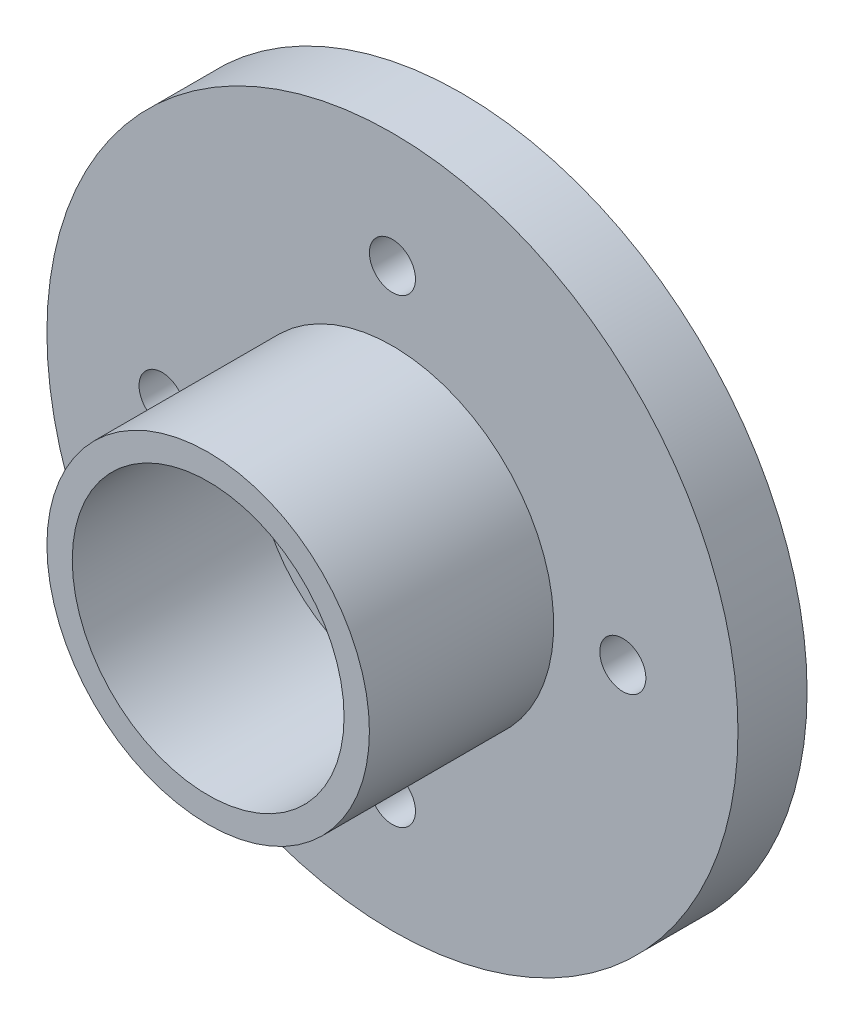
SolidWorks part; units mm, degrees
ref_plane "Plan de face" through (0, 0, 0) normal (0, 0, 1) x (1, 0, 0)
ref_plane "Plan de dessus" through (0, 0, 0) normal (0, 1, 0) x (1, 0, 0)
ref_plane "Plan de droite" through (0, 0, 0) normal (1, 0, 0) x (0, 0, -1)
sketch "Esquisse1" plane through (0, 0, 0) normal (0, 0, 1) x (1, 0, 0)
  circle A0 centre (0, 0) radius 2.95
  circle A1 centre (0, 0) radius 3.5
  dimension "D1" = 5.9
  dimension "D2" = 7
extrude "Boss.-Extru.1" add sketch "Esquisse1" along normal blind 4
sketch "Esquisse2" plane through (0, 0, 0) normal (0, 0, -1) x (-1, 0, 0)
  circle A0 centre (0, 0) radius 7.5
  dimension "D1" = 15
extrude "Boss.-Extru.2" add sketch "Esquisse2" along normal blind 1.5
sketch "Esquisse3" plane through (0, 0, -1.5) normal (0, 0, -1) x (-1, 0, 0)
  line L0 (8.0367, 0) -> (-7.2343, 0) construction
  line L1 (0, 8.9957) -> (0, -8.5968) construction
  circle A0 centre (0, 5) radius 0.5
  circle A1 centre (5, 0) radius 0.5
  circle A2 centre (0, 0) radius 7.5 construction
  circle A3 centre (0, -5) radius 0.5
  circle A4 centre (-5, 0) radius 0.5
  point P9 (0, 0)
  dimension "D1" = 1
  dimension "D2" = 1
  dimension "D3" = 5
  dimension "D4" = 5
extrude "Enlèv. mat.-Extru.3" cut sketch "Esquisse3" against normal blind 2
